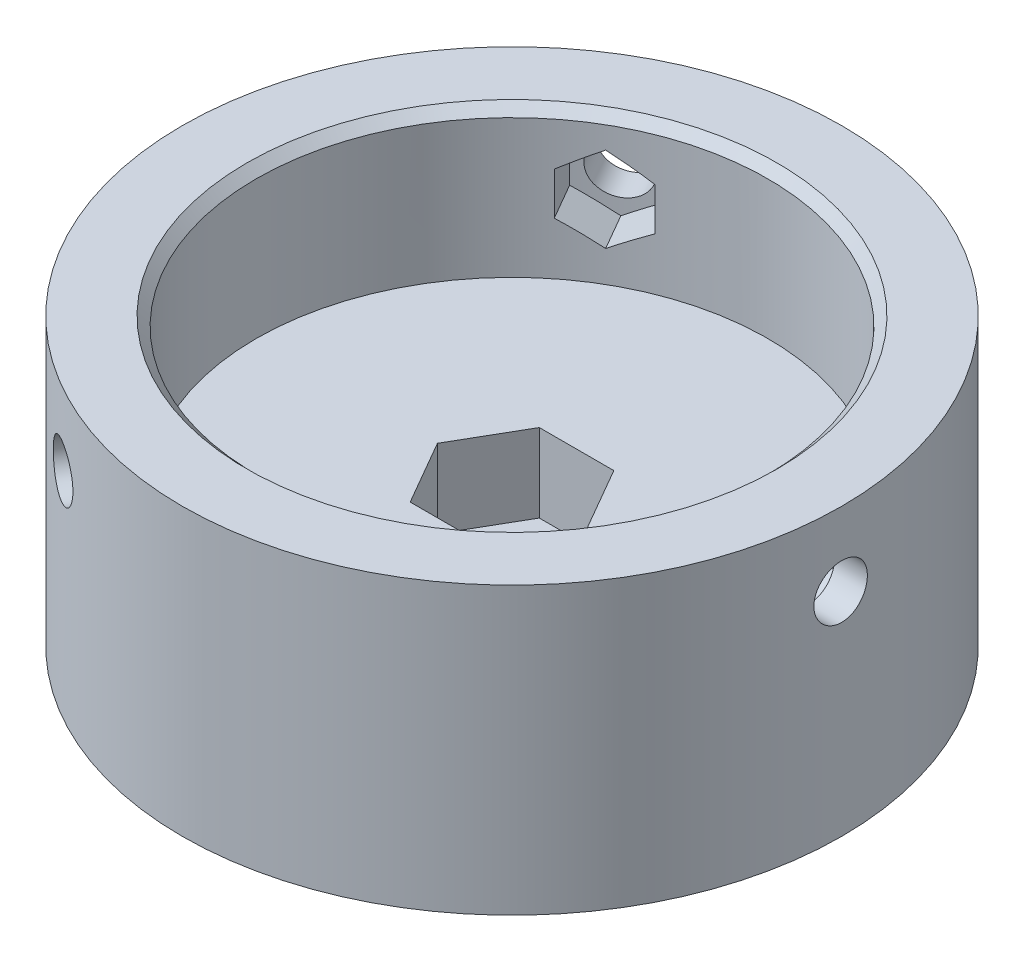
SolidWorks part; units mm, degrees
ref_plane "前基準面" through (0, 0, 0) normal (0, 0, 1) x (1, 0, 0)
ref_plane "上基準面" through (0, 0, 0) normal (0, 1, 0) x (1, 0, 0)
ref_plane "右基準面" through (0, 0, 0) normal (1, 0, 0) x (0, 0, -1)
sketch "草圖1" plane through (0, 0, 0) normal (0, 0, 1) x (1, 0, 0)
  line L0 (0, 38.1357) -> (0, 0) construction
  line L1 (0, 15) -> (0, 0)
  line L2 (0, 0) -> (35.75, 0)
  line L3 (35.75, 0) -> (35.75, 31)
  line L4 (35.75, 31) -> (27.75, 31)
  line L5 (27.75, 31) -> (27.75, 15)
  line L6 (27.75, 15) -> (0, 15)
  dimension "D1" = 55.5
  dimension "D2" = 8
  dimension "D3" = 16
  dimension "D4" = 15
  dimension "D5" = 31
revolve "旋轉1" add sketch "草圖1" angle 360 about L0
sketch "草圖2" plane through (0, 0, 0) normal (1, 0, 0) x (0, 0, -1)
  line L1 (27.75, 15) -> (-27.75, 15) construction
  line L2 (27.75, 31) -> (-27.75, 31) construction
  line L4 (27.75, 15) -> (-27.75, 15) construction
  line L5 (27.75, 31) -> (-27.75, 31) construction
  line L6 (0, 31) -> (0, 15) construction
  line L8 (0, 27.6188) -> (-4, 25.3094)
  line L9 (-4, 25.3094) -> (-4, 20.6906)
  line L10 (-4, 20.6906) -> (0, 18.3812)
  line L11 (0, 18.3812) -> (4, 20.6906)
  line L12 (4, 20.6906) -> (4, 25.3094)
  line L13 (4, 25.3094) -> (0, 27.6188)
  circle A0 centre (0, 23) radius 4 construction
  dimension "D1" = 8
extrude "除料-伸長1" cut sketch "草圖2" along normal offset from surface (32.001 mm away) 4.5
sketch "草圖3" plane through (0, 0, 0) normal (1, 0, 0) x (0, 0, -1)
  circle A0 centre (0, 23) radius 2.9
  dimension "D1" = 5.8
extrude "除料-伸長2" cut sketch "草圖3" along normal through all
pattern_circular "環狀複製排列1" count 3 over 360 about axis through (0, 0, 0) along (0, 1, 0) of "除料-伸長1", "除料-伸長2"
sketch "草圖6" plane through (0, 15, 0) normal (0, 1, 0) x (1, 0, 0)
  line L1 (8.0829, 0) -> (4.0415, 7)
  line L2 (4.0415, 7) -> (-4.0415, 7)
  line L3 (-4.0415, 7) -> (-8.0829, 0)
  line L4 (-8.0829, 0) -> (-4.0415, -7)
  line L5 (-4.0415, -7) -> (4.0415, -7)
  line L6 (4.0415, -7) -> (8.0829, 0)
  circle A0 centre (0, 0) radius 7 construction
  dimension "D1" = 14
extrude "除料-伸長5" cut sketch "草圖6" against normal blind 8.5
hole_wizard "3/8 餘隙孔1" positions "草圖7" profile "草圖8" hole size "3/8" standard "Ansi Inch"
sketch "草圖7" plane through (0, 0, 0) normal (0, -1, 0) x (-1, 0, 0)
  point P0 (0, 0)
sketch "草圖8" plane through (0, 0, 0) normal (1, 0, 0) x (0, 0, -1)
  line L0 (0, 0) -> (0, 13.0997)
  line L1 (0, 13.0997) -> (5.1587, 10)
  line L2 (5.1587, 10) -> (5.1587, 0)
  line L5 (5.1587, 0) -> (0, 0)
  line L10 (0, 13.0997) -> (-5.1587, 10) construction
  line L11 (0, -6.35) -> (0, 107.95) construction
  dimension "鑽孔直徑" = 10.3175
  dimension "鑽孔深度" = 10
  dimension "導頭角度" = 118
chamfer "導角1" distance 1 angle 45 1 edges at (-27.75, 31, 0)
